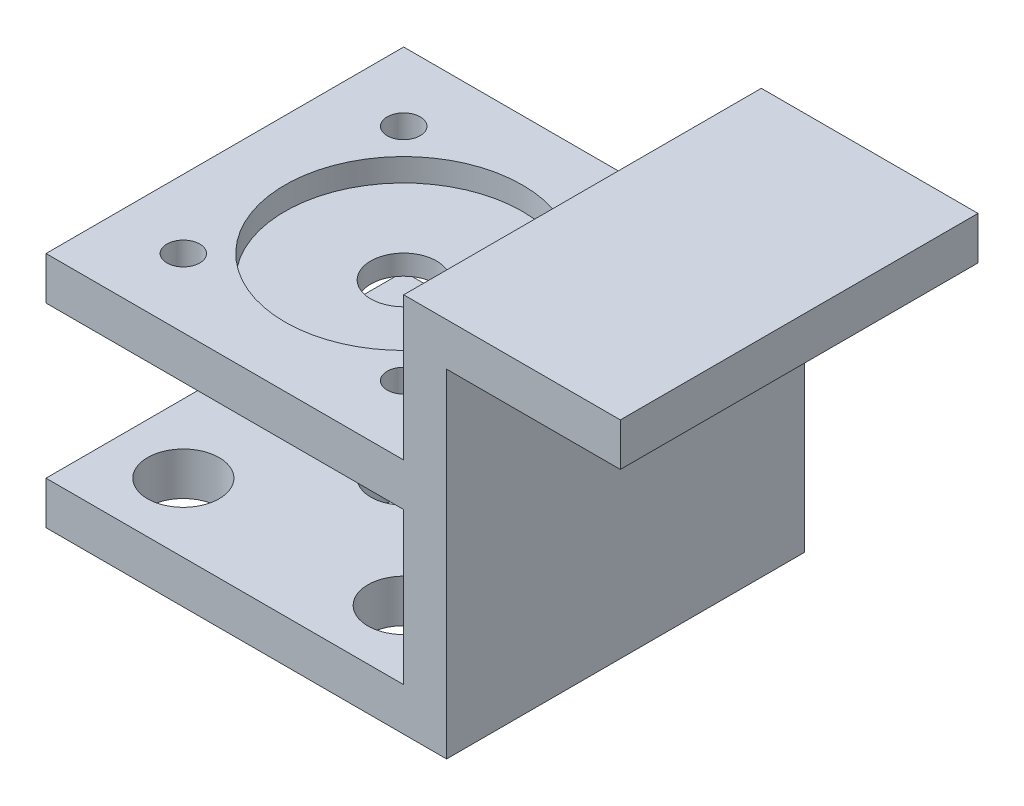
SolidWorks part; units mm, degrees
ref_plane "Front Plane" through (0, 0, 0) normal (0, 0, 1) x (1, 0, 0)
ref_plane "Top Plane" through (0, 0, 0) normal (0, 1, 0) x (1, 0, 0)
ref_plane "Right Plane" through (0, 0, 0) normal (1, 0, 0) x (0, 0, -1)
sketch "Sketch1" plane through (0, 0, 0) normal (0, 1, 0) x (1, 0, 0)
  line L1 (7.7, 7.7) -> (-7.7, 7.7) construction
  line L2 (7.7, 7.7) -> (7.7, -7.7) construction
  line L3 (7.7, -7.7) -> (-7.7, -7.7) construction
  line L4 (-7.7, 7.7) -> (-7.7, -7.7) construction
  line L5 (7.7, 7.7) -> (-7.7, -7.7) construction
  line L6 (7.7, -7.7) -> (-7.7, 7.7) construction
  line L7 (12.5, 12.5) -> (-12.5, 12.5)
  line L8 (12.5, 12.5) -> (12.5, -12.5) construction
  line L9 (12.5, -12.5) -> (-12.5, -12.5)
  line L10 (-12.5, 12.5) -> (-12.5, -12.5)
  line L11 (12.5, 12.5) -> (-12.5, -12.5) construction
  line L12 (12.5, -12.5) -> (-12.5, 12.5) construction
  line L13 (12.5, 12.5) -> (15.5, 12.5)
  line L14 (12.5, 12.5) -> (12.5, -12.5) construction
  line L15 (12.5, -12.5) -> (15.5, -12.5)
  line L16 (15.5, 12.5) -> (15.5, -12.5)
  circle A0 centre (-7.7, 7.7) radius 1.15
  circle A1 centre (-7.7, -7.7) radius 1.15
  circle A2 centre (7.7, -7.7) radius 1.15
  circle A3 centre (7.7, 7.7) radius 1.15
  point P0 (0, 0)
  point P10 (0, 0)
  dimension "D2" = 2.3
  dimension "D1" = 15.4
  dimension "D3" = 25
  dimension "D4" = 25
  dimension "D5" = 3
extrude "Boss-Extrude1" add sketch "Sketch1" along normal blind 3
sketch "Sketch2" plane through (0, 3, 0) normal (0, 1, 0) x (1, 0, 0)
  line L0 (-12.5, -12.5) -> (15.5, -12.5) construction
  line L1 (15.5, 12.5) -> (12.5, 12.5)
  line L2 (15.5, 12.5) -> (15.5, -12.5)
  line L3 (15.5, -12.5) -> (12.5, -12.5)
  line L4 (12.5, 12.5) -> (12.5, -12.5)
  dimension "D1" = 3
extrude "Boss-Extrude2" add sketch "Sketch2" along normal offset from surface (7 mm away) 10 up to face at (7.7, 0, 8.85)
sketch "Sketch3" plane through (0, 10, 0) normal (0, 1, 0) x (1, 0, 0)
  line L0 (15.5, -12.5) -> (12.5, -12.5) construction
  line L1 (12.5, 12.5) -> (27.6439, 12.5)
  line L2 (12.5, 12.5) -> (12.5, -12.5)
  line L3 (12.5, -12.5) -> (27.6439, -12.5)
  line L4 (27.6439, 12.5) -> (27.6439, -12.5)
extrude "Boss-Extrude3" add sketch "Sketch3" along normal blind 3
sketch "Sketch4" plane through (0, 3, 0) normal (0, 1, 0) x (1, 0, 0)
  circle A0 centre (0, 0) radius 8.3
  dimension "D1" = 16.6
extrude "Cut-Extrude1" cut sketch "Sketch4" against normal blind 1.6
sketch "Sketch5" plane through (0, 1.4, 0) normal (0, 1, 0) x (1, 0, 0)
  circle A0 centre (0, 0) radius 2.3
  dimension "D1" = 4.6
extrude "Cut-Extrude2" cut sketch "Sketch5" against normal through all
sketch "Sketch6" plane through (0, 0, 0) normal (0, -1, 0) x (1, 0, 0)
  line L0 (15.5, -12.5) -> (-12.5, -12.5) construction
  line L1 (15.5, 12.5) -> (12.5, 12.5)
  line L2 (15.5, 12.5) -> (15.5, -12.5)
  line L3 (15.5, -12.5) -> (12.5, -12.5)
  line L4 (12.5, 12.5) -> (12.5, -12.5)
extrude "Boss-Extrude4" add sketch "Sketch6" along normal blind 10.6
sketch "Sketch7" plane through (0, -10.6, 0) normal (0, -1, 0) x (1, 0, 0)
  line L1 (15.5, 12.5) -> (-12.5, 12.5)
  line L2 (15.5, 12.5) -> (15.5, -12.5)
  line L3 (15.5, -12.5) -> (-12.5, -12.5)
  line L4 (-12.5, 12.5) -> (-12.5, -12.5)
  circle A0 centre (0, 0) radius 2.3 construction
  circle A1 centre (0, 0) radius 2.3
  circle A2 centre (-7.7, 7.7) radius 1.15 construction
  circle A3 centre (-7.7, -7.7) radius 1.15 construction
  circle A5 centre (7.7, -7.7) radius 1.15 construction
  circle A8 centre (7.7, 7.7) radius 1.15 construction
  circle A24 centre (7.7, -7.7) radius 1.15 construction
  circle A25 centre (-7.7, -7.7) radius 1.15 construction
  circle A26 centre (7.7, 7.7) radius 1.15 construction
  circle A27 centre (-7.7, 7.7) radius 1.15 construction
  circle A28 centre (-7.7, 7.7) radius 2.5
  circle A29 centre (-7.7, -7.7) radius 2.5
  circle A30 centre (7.7, -7.7) radius 2.5
  circle A31 centre (7.7, 7.7) radius 2.5
  dimension "D1" = 5
extrude "Boss-Extrude5" add sketch "Sketch7" along normal blind 3
